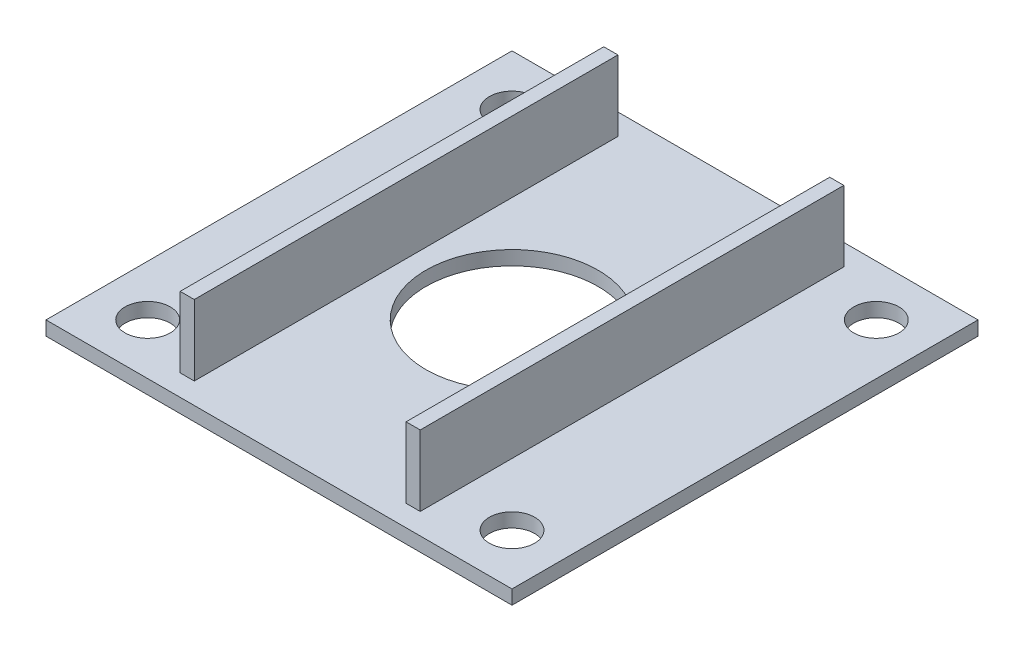
SolidWorks part; units mm, degrees
ref_plane "前视基准面" through (0, 0, 0) normal (0, 0, 1) x (1, 0, 0)
ref_plane "上视基准面" through (0, 0, 0) normal (0, 1, 0) x (1, 0, 0)
ref_plane "右视基准面" through (0, 0, 0) normal (1, 0, 0) x (0, 0, -1)
sketch "草图1" plane through (0, 0, 0) normal (0, 1, 0) x (1, 0, 0)
  line L1 (-16.5, 16.5) -> (16.5, 16.5)
  line L2 (-16.5, 16.5) -> (-16.5, -16.5)
  line L3 (-16.5, -16.5) -> (16.5, -16.5)
  line L4 (16.5, 16.5) -> (16.5, -16.5)
  line L5 (-16.5, 16.5) -> (16.5, -16.5) construction
  line L6 (-16.5, -16.5) -> (16.5, 16.5) construction
  point P0 (0, 0)
  dimension "D1" = 33
  dimension "D2" = 33
extrude "凸台-拉伸1" add sketch "草图1" along normal blind 1
sketch "草图2" plane through (0, 1, 0) normal (0, 1, 0) x (1, 0, 0)
  line L1 (16.5, 16.5) -> (-16.5, 16.5) construction
  line L2 (-16.5, 16.5) -> (-16.5, -16.5) construction
  line L3 (0, 0) -> (0, 21.0785) construction
  line L4 (0, 0) -> (-23.3999, 0) construction
  circle A0 centre (0, 0) radius 6.1
  circle A1 centre (-12.9, 12.9) radius 1.6
  circle A2 centre (12.9, 12.9) radius 1.6
  circle A3 centre (12.9, -12.9) radius 1.6
  circle A4 centre (-12.9, -12.9) radius 1.6
  circle A5 centre (-12.9, 12.9) radius 2.6 construction
  dimension "D1" = 12.2
  dimension "D2" = 3.2
  dimension "D3" = 2
  dimension "D4" = 2
  dimension "D5" = 5.2
extrude "切除-拉伸1" cut sketch "草图2" against normal through all
sketch "草图3" plane through (0, 1, 0) normal (0, 1, 0) x (1, 0, 0)
  line L0 (0, 0) -> (0, 12.67) construction
  line L1 (-8.5, 15) -> (-7.5, 15)
  line L2 (-8.5, 15) -> (-8.5, -15)
  line L3 (-8.5, -15) -> (-7.5, -15)
  line L4 (-7.5, 15) -> (-7.5, -15)
  line L9 (7.5, 15) -> (7.5, -15)
  line L10 (8.5, -15) -> (7.5, -15)
  line L11 (8.5, 15) -> (8.5, -15)
  line L12 (8.5, 15) -> (7.5, 15)
  line L13 (0, 0) -> (4.63, 0) construction
  circle A0 centre (-12.9, 12.9) radius 2.6 construction
  dimension "D4" = 5.2
  dimension "D1" = 15
  dimension "D2" = 1
  dimension "D3" = 30
extrude "凸台-拉伸2" add sketch "草图3" along normal blind 5
